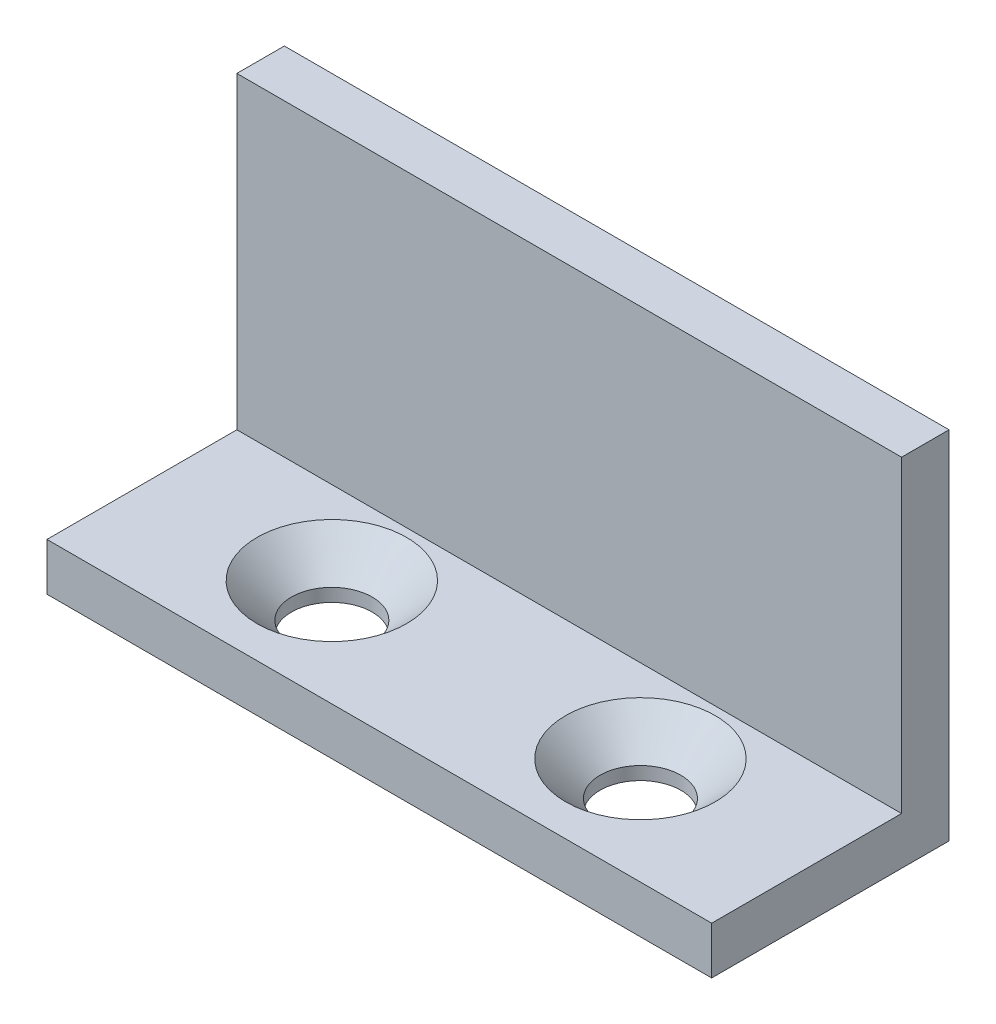
SolidWorks part; units mm, degrees
ref_plane "Front Plane" through (0, 0, 0) normal (0, 0, 1) x (1, 0, 0)
ref_plane "Top Plane" through (0, 0, 0) normal (0, 1, 0) x (1, 0, 0)
ref_plane "Right Plane" through (0, 0, 0) normal (1, 0, 0) x (0, 0, -1)
sketch "Sketch1" plane through (0, 0, 0) normal (1, 0, 0) x (0, 0, -1)
  line L0 (-10, 0) -> (0, 0)
  line L1 (0, 0) -> (0, 15)
  line L2 (-10, 2) -> (-2, 2)
  line L3 (-2, 2) -> (-2, 15)
  line L4 (-2, 15) -> (0, 15)
  line L5 (-10, 2) -> (-10, 0)
  dimension "D1" = 15
  dimension "D2" = 10
  dimension "D3" = 2
extrude "Boss-Extrude1" add sketch "Sketch1" along normal blind 28
sketch "Sketch2" plane through (0, 2, 0) normal (0, 1, 0) x (1, 0, 0)
  line L0 (7.5, -5.5) -> (20.5, -5.5) construction
  line L1 (0, -2) -> (0, -10) construction
  line L2 (28, -10) -> (0, -10) construction
  dimension "D1" = 13
  dimension "D2" = 7.5
  dimension "D3" = 4.5
hole_wizard "CSK for M3 Countersunk Flat Head Screw1" positions "3DSketch1" profile "Sketch3" countersink size "M3" standard "DIN" end condition through all
sketch3d "3DSketch1"
  point P0 (7.5, 2, 5.5)
  point P3 (20.5, 2, 5.5)
sketch "Sketch3" plane through (7.5, 2, 5.5) normal (1, 0, 0) x (0, 0, 1)
  line L0 (0, 0) -> (0, 2)
  line L1 (0, 2) -> (1.7, 2)
  line L2 (1.7, 2) -> (1.7, 1.45)
  line L3 (1.7, 1.45) -> (3.15, 0)
  line L5 (3.15, 0) -> (0, 0)
  line L6 (-1.7, 1.45) -> (-3.15, 0) construction
  line L11 (0, -6.35) -> (0, 107.95) construction
  dimension "Thru Hole Dia." = 3.4
  dimension "Thru Hole Depth" = 2
  dimension "Near C'Sink Dia." = 6.3
  dimension "Near C'Sink Angle" = 90
